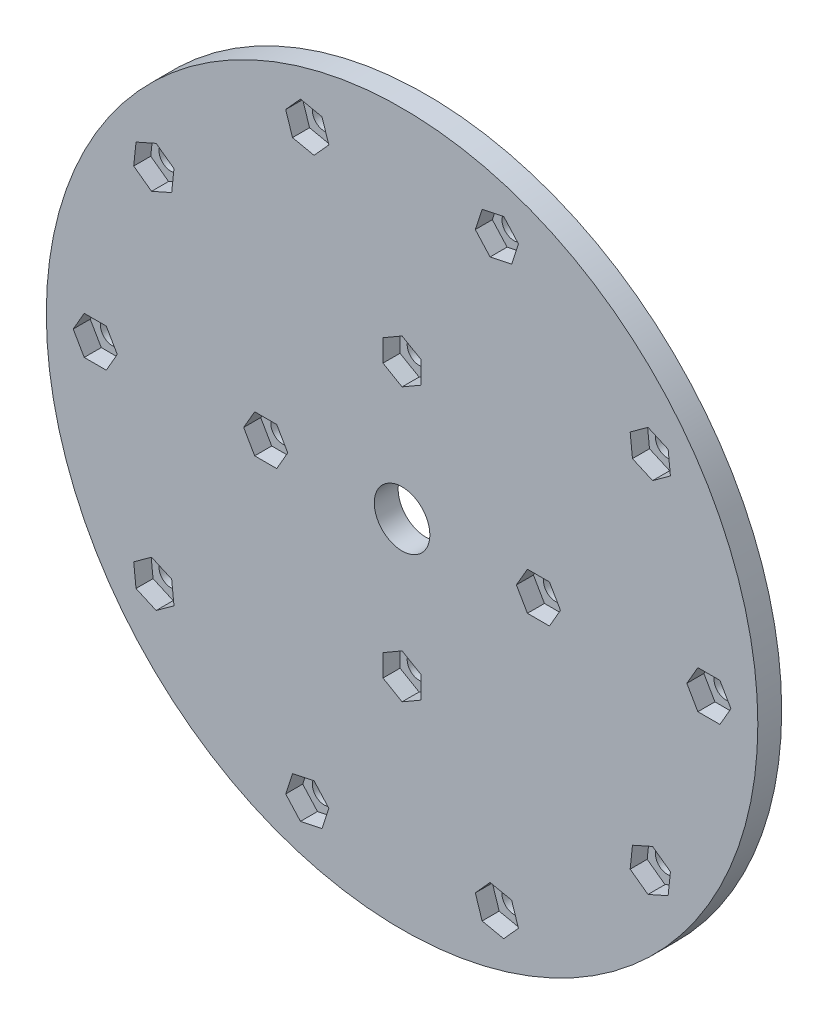
SolidWorks part; units mm, degrees
ref_plane "Front Plane" through (0, 0, 0) normal (0, 0, 1) x (1, 0, 0)
ref_plane "Top Plane" through (0, 0, 0) normal (0, 1, 0) x (1, 0, 0)
ref_plane "Right Plane" through (0, 0, 0) normal (1, 0, 0) x (0, 0, -1)
sketch "Sketch2" plane through (0, 0, 0) normal (0, 0, 1) x (1, 0, 0)
  circle A0 centre (-50.9296, 50.9296) radius 52.18
  circle A2 centre (-50.9296, 50.9296) radius 4.075
  point P2 (0, 0)
  point P4 (0, 0)
  point P5 (0, 0)
  dimension "D1" = 104.36
  dimension "D2" = 8.15
extrude "Boss-Extrude2" add sketch "Sketch2" along normal blind 3.5
ref_plane "Plane2" through (0, 0, 3.5) normal (0, 0, 1) x (1, 0, 0)
sketch "Sketch3" plane through (0, 0, 3.5) normal (0, 0, 1) x (1, 0, 0)
  line L0 (-50.9296, 50.9296) -> (-5.9296, 50.9296) construction
  line L1 (-53.7296, 32.5462) -> (-53.7296, 29.313)
  line L2 (-32.5462, 48.1296) -> (-29.313, 48.1296)
  line L3 (-29.313, 48.1296) -> (-27.6964, 50.9296)
  line L4 (-27.6964, 50.9296) -> (-29.313, 53.7296)
  line L5 (-29.313, 53.7296) -> (-32.5462, 53.7296)
  line L6 (-32.5462, 53.7296) -> (-34.1627, 50.9296)
  line L7 (-34.1627, 50.9296) -> (-32.5462, 48.1296)
  line L8 (-7.5462, 48.1296) -> (-4.313, 48.1296)
  line L9 (-4.313, 48.1296) -> (-2.6964, 50.9296)
  line L10 (-2.6964, 50.9296) -> (-4.313, 53.7296)
  line L11 (-4.313, 53.7296) -> (-7.5462, 53.7296)
  line L12 (-7.5462, 53.7296) -> (-9.1627, 50.9296)
  line L13 (-9.1627, 50.9296) -> (-7.5462, 48.1296)
  line L14 (-53.7296, 29.313) -> (-50.9296, 27.6964)
  line L15 (-50.9296, 27.6964) -> (-48.1296, 29.313)
  line L16 (-48.1296, 29.313) -> (-48.1296, 32.5462)
  line L17 (-48.1296, 32.5462) -> (-50.9296, 34.1627)
  line L18 (-50.9296, 34.1627) -> (-53.7296, 32.5462)
  line L19 (-69.313, 53.7296) -> (-72.5462, 53.7296)
  line L20 (-72.5462, 53.7296) -> (-74.1627, 50.9296)
  line L21 (-74.1627, 50.9296) -> (-72.5462, 48.1296)
  line L22 (-72.5462, 48.1296) -> (-69.313, 48.1296)
  line L23 (-69.313, 48.1296) -> (-67.6964, 50.9296)
  line L24 (-67.6964, 50.9296) -> (-69.313, 53.7296)
  line L25 (-48.1296, 69.313) -> (-48.1296, 72.5462)
  line L26 (-48.1296, 72.5462) -> (-50.9296, 74.1627)
  line L27 (-50.9296, 74.1627) -> (-53.7296, 72.5462)
  line L28 (-53.7296, 72.5462) -> (-53.7296, 69.313)
  line L29 (-53.7296, 69.313) -> (-50.9296, 67.6964)
  line L30 (-50.9296, 67.6964) -> (-48.1296, 69.313)
  line L31 (-17.4775, 23.1642) -> (-14.8618, 21.2638)
  line L32 (-14.8618, 21.2638) -> (-11.9081, 22.5788)
  line L33 (-11.9081, 22.5788) -> (-11.5702, 25.7943)
  line L34 (-11.5702, 25.7943) -> (-14.1859, 27.6947)
  line L35 (-14.1859, 27.6947) -> (-17.1395, 26.3797)
  line L36 (-17.1395, 26.3797) -> (-17.4775, 23.1642)
  line L37 (-40.1863, 8.8043) -> (-39.1872, 5.7293)
  line L38 (-39.1872, 5.7293) -> (-36.0247, 5.0571)
  line L39 (-36.0247, 5.0571) -> (-33.8613, 7.4598)
  line L40 (-33.8613, 7.4598) -> (-34.8604, 10.5347)
  line L41 (-34.8604, 10.5347) -> (-38.0229, 11.207)
  line L42 (-38.0229, 11.207) -> (-40.1863, 8.8043)
  line L43 (-66.9988, 10.5347) -> (-67.9979, 7.4598)
  line L44 (-67.9979, 7.4598) -> (-65.8344, 5.0571)
  line L45 (-65.8344, 5.0571) -> (-62.6719, 5.7293)
  line L46 (-62.6719, 5.7293) -> (-61.6728, 8.8043)
  line L47 (-61.6728, 8.8043) -> (-63.8362, 11.207)
  line L48 (-63.8362, 11.207) -> (-66.9988, 10.5347)
  line L49 (-87.6733, 27.6947) -> (-90.289, 25.7943)
  line L50 (-90.289, 25.7943) -> (-89.951, 22.5788)
  line L51 (-89.951, 22.5788) -> (-86.9974, 21.2638)
  line L52 (-86.9974, 21.2638) -> (-84.3817, 23.1642)
  line L53 (-84.3817, 23.1642) -> (-84.7197, 26.3797)
  line L54 (-84.7197, 26.3797) -> (-87.6733, 27.6947)
  line L55 (-94.313, 53.7296) -> (-97.5462, 53.7296)
  line L56 (-97.5462, 53.7296) -> (-99.1627, 50.9296)
  line L57 (-99.1627, 50.9296) -> (-97.5462, 48.1296)
  line L58 (-97.5462, 48.1296) -> (-94.313, 48.1296)
  line L59 (-94.313, 48.1296) -> (-92.6964, 50.9296)
  line L60 (-92.6964, 50.9296) -> (-94.313, 53.7296)
  line L61 (-84.3817, 78.695) -> (-86.9974, 80.5954)
  line L62 (-86.9974, 80.5954) -> (-89.951, 79.2803)
  line L63 (-89.951, 79.2803) -> (-90.289, 76.0649)
  line L64 (-90.289, 76.0649) -> (-87.6733, 74.1645)
  line L65 (-87.6733, 74.1645) -> (-84.7197, 75.4795)
  line L66 (-84.7197, 75.4795) -> (-84.3817, 78.695)
  line L67 (-61.6728, 93.0549) -> (-62.6719, 96.1298)
  line L68 (-62.6719, 96.1298) -> (-65.8344, 96.802)
  line L69 (-65.8344, 96.802) -> (-67.9979, 94.3993)
  line L70 (-67.9979, 94.3993) -> (-66.9988, 91.3244)
  line L71 (-66.9988, 91.3244) -> (-63.8362, 90.6522)
  line L72 (-63.8362, 90.6522) -> (-61.6728, 93.0549)
  line L73 (-34.8604, 91.3244) -> (-33.8613, 94.3993)
  line L74 (-33.8613, 94.3993) -> (-36.0247, 96.802)
  line L75 (-36.0247, 96.802) -> (-39.1872, 96.1298)
  line L76 (-39.1872, 96.1298) -> (-40.1863, 93.0549)
  line L77 (-40.1863, 93.0549) -> (-38.0229, 90.6522)
  line L78 (-38.0229, 90.6522) -> (-34.8604, 91.3244)
  line L79 (-14.1859, 74.1645) -> (-11.5702, 76.0649)
  line L80 (-11.5702, 76.0649) -> (-11.9081, 79.2803)
  line L81 (-11.9081, 79.2803) -> (-14.8618, 80.5954)
  line L82 (-14.8618, 80.5954) -> (-17.4775, 78.695)
  line L83 (-17.4775, 78.695) -> (-17.1395, 75.4795)
  line L84 (-17.1395, 75.4795) -> (-14.1859, 74.1645)
  circle A14 centre (-50.9296, 50.9296) radius 4.075 construction
  circle A15 centre (-30.9296, 50.9296) radius 2.8 construction
  circle A16 centre (-5.9296, 50.9296) radius 2.8 construction
  point P24 (-50.9296, 50.9296)
  point P30 (-50.9296, 50.9296)
  point P34 (-50.9296, 50.9296)
  point P96 (-50.9296, 50.9296)
  dimension "D1" = 5.6
  dimension "D6" = 10
  dimension "D4" = 5.6
  dimension "D2" = 45
  dimension "D3" = 20
  dimension "D5" = 4
extrude "Cut-Extrude1" cut sketch "Sketch3" against normal blind 2.5
sketch "Sketch4" plane through (0, 0, 3.5) normal (0, 0, 1) x (1, 0, 0)
  line L0 (-50.9296, 50.9296) -> (-5.9296, 50.9296) construction
  circle A0 centre (-30.9296, 50.9296) radius 1.75
  circle A1 centre (-5.9296, 50.9296) radius 1.75
  circle A2 centre (-50.9296, 30.9296) radius 1.75
  circle A3 centre (-70.9296, 50.9296) radius 1.75
  circle A4 centre (-50.9296, 70.9296) radius 1.75
  circle A5 centre (-14.5238, 24.4792) radius 1.75
  circle A6 centre (-37.0238, 8.132) radius 1.75
  circle A7 centre (-64.8353, 8.132) radius 1.75
  circle A8 centre (-87.3353, 24.4792) radius 1.75
  circle A9 centre (-95.9296, 50.9296) radius 1.75
  circle A10 centre (-87.3353, 77.3799) radius 1.75
  circle A11 centre (-64.8353, 93.7271) radius 1.75
  circle A12 centre (-37.0238, 93.7271) radius 1.75
  circle A13 centre (-14.5238, 77.3799) radius 1.75
  point P15 (-50.9296, 50.9296)
  point P34 (-50.9296, 50.9296)
  dimension "D3" = 3.5
  dimension "D4" = 3.5
  dimension "D1" = 45
  dimension "D2" = 20
  dimension "D5" = 4
  dimension "D6" = 10
extrude "Cut-Extrude2" cut sketch "Sketch4" against normal through all
